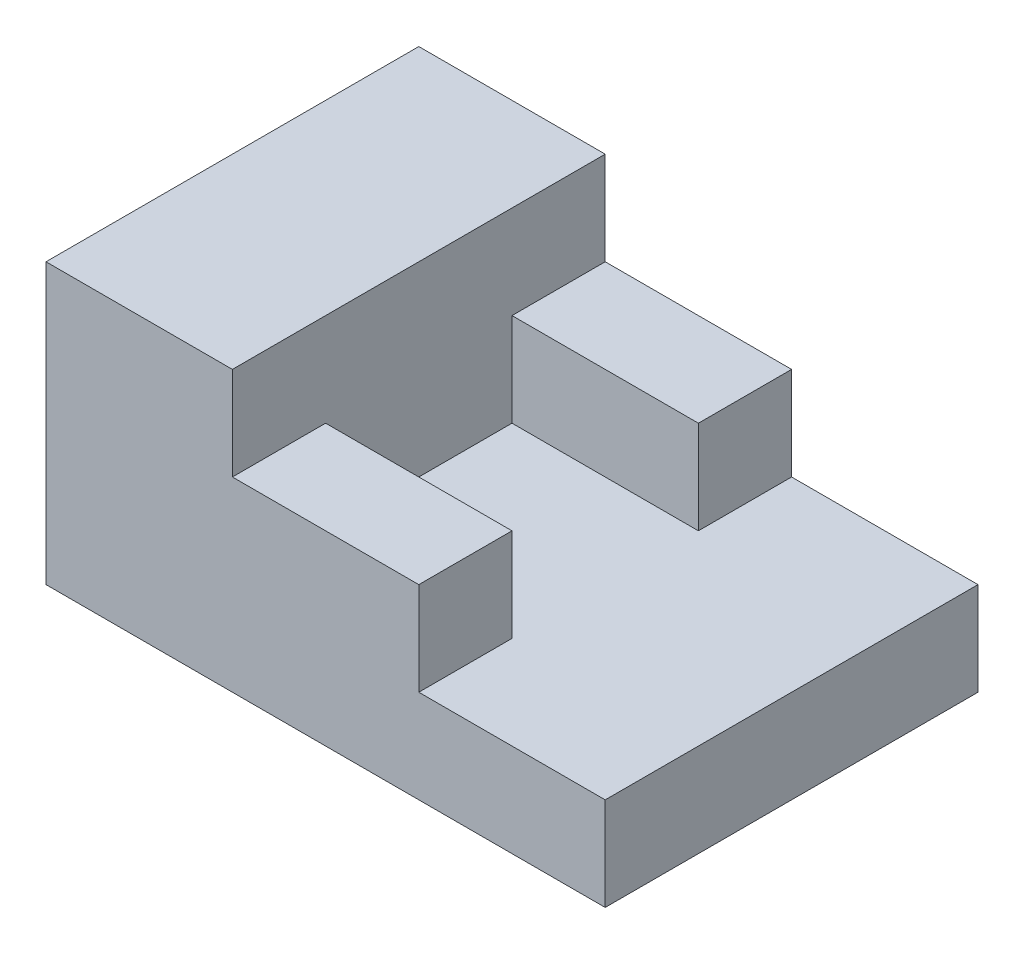
SolidWorks part; units mm, degrees
ref_plane "前基準面" through (0, 0, 0) normal (0, 0, 1) x (1, 0, 0)
ref_plane "上基準面" through (0, 0, 0) normal (0, 1, 0) x (1, 0, 0)
ref_plane "右基準面" through (0, 0, 0) normal (1, 0, 0) x (0, 0, -1)
sketch "草圖1" plane through (0, 0, 0) normal (0, 0, 1) x (1, 0, 0)
  line L1 (0, 0) -> (10, 0)
  line L2 (0, 0) -> (0, 15)
  line L3 (0, 15) -> (10, 15)
  line L4 (10, 0) -> (10, 15)
  line L5 (10, 0) -> (20, 0)
  line L6 (10, 0) -> (10, 10)
  line L7 (10, 10) -> (20, 10)
  line L8 (20, 0) -> (20, 10)
  line L9 (20, 0) -> (30, 0)
  line L10 (20, 0) -> (20, 5)
  line L11 (20, 5) -> (30, 5)
  line L12 (30, 0) -> (30, 5)
  dimension "D1" = 15
  dimension "D2" = 10
  dimension "D3" = 30
  dimension "D4" = 10
  dimension "D5" = 5
  dimension "D6" = 10
extrude "填料-伸長1" add sketch "草圖1" against normal blind 20 contours L1 L4 L3 L2 | L5 L8 L7 L4 | L9 L12 L11 L8
sketch "草圖2" plane through (0, 10, 0) normal (0, 1, 0) x (1, 0, 0)
  line L0 (10, 20) -> (10, 0) construction
  line L1 (10, 15) -> (20, 15)
  line L2 (10, 15) -> (10, 5)
  line L3 (10, 5) -> (20, 5)
  line L4 (20, 15) -> (20, 5)
  line L5 (20, 20) -> (20, 0) construction
  line L6 (10, 20) -> (20, 20) construction
  line L7 (10, 0) -> (20, 0) construction
  dimension "D1" = 5
  dimension "D2" = 5
extrude "除料-伸長1" cut sketch "草圖2" against normal up to surface (5 mm away) up to face at (25, 5, -10)
